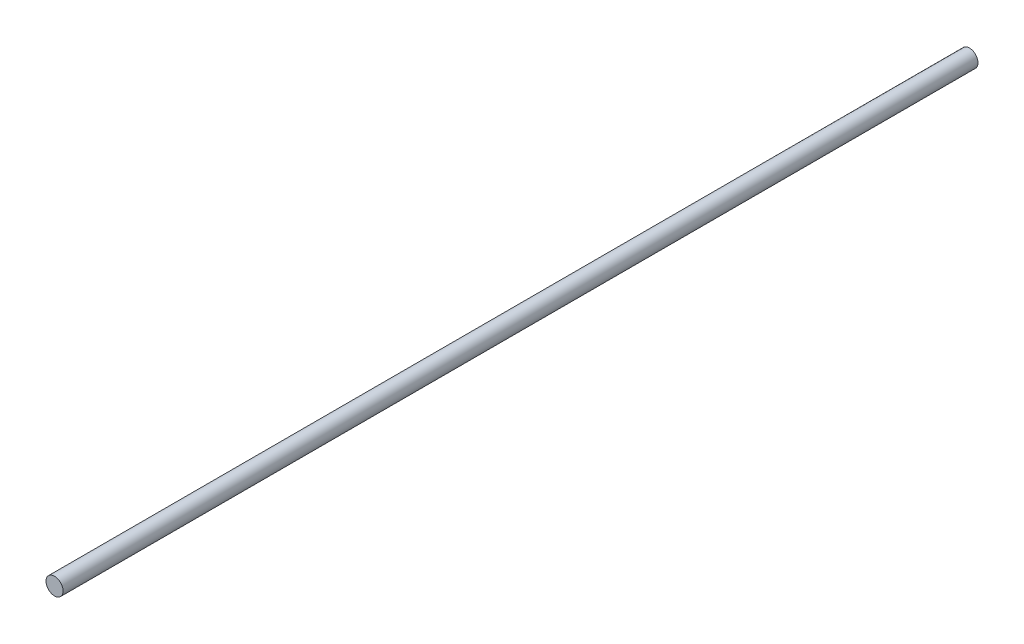
SolidWorks part; units mm, degrees
ref_plane "前视基准面" through (0, 0, 0) normal (0, 0, 1) x (1, 0, 0)
ref_plane "上视基准面" through (0, 0, 0) normal (0, 1, 0) x (1, 0, 0)
ref_plane "右视基准面" through (0, 0, 0) normal (1, 0, 0) x (0, 0, -1)
other "Configuration Table"
sketch "草图6" plane through (0, 0, 0) normal (0, 0, 1) x (1, 0, 0)
  circle A0 centre (0, 0) radius 1.6
  point P3 (0, 0)
extrude "凸台-拉伸3" add sketch "草图6" along normal blind 171
